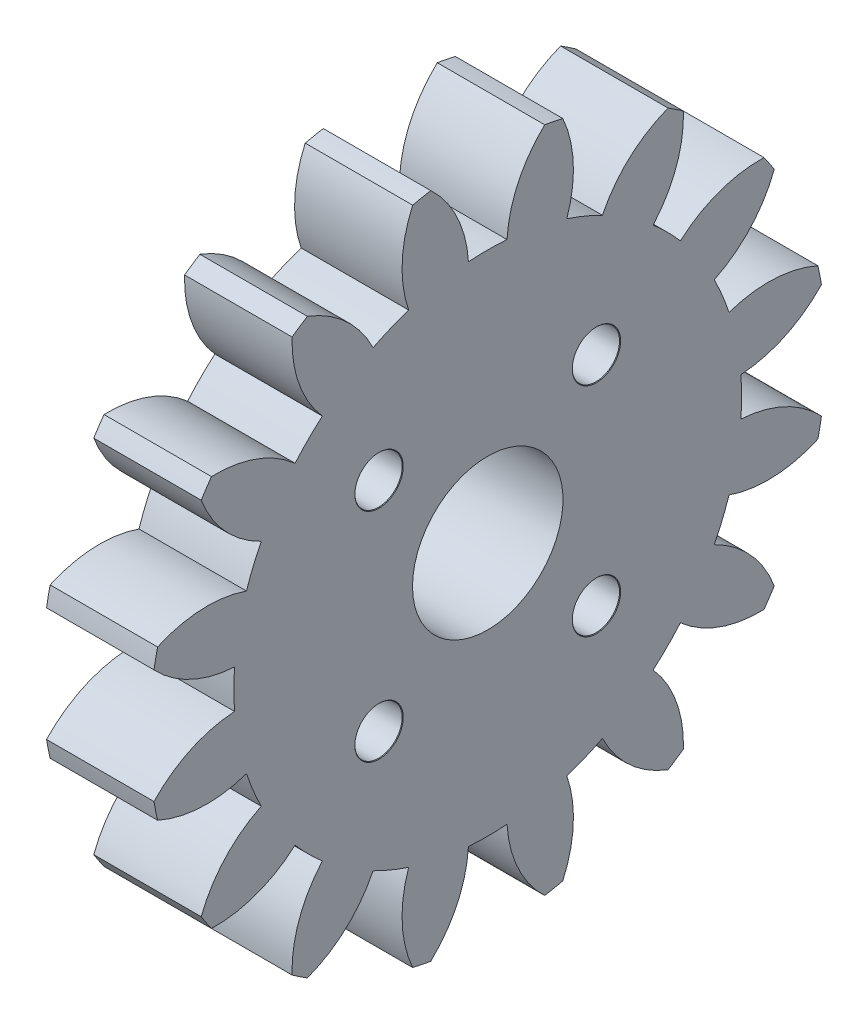
SolidWorks part; units mm, degrees
ref_plane "Plane1" through (0, 0, 0) normal (0, 0, 1) x (1, 0, 0)
ref_plane "Plane2" through (0, 0, 0) normal (0, 1, 0) x (1, 0, 0)
ref_plane "Plane3" through (0, 0, 0) normal (1, 0, 0) x (0, 0, -1)
other "Configuration Table"
sketch "HoldingSke" plane through (0, 0, 0) normal (0, 1, 0) x (1, 0, 0)
  line L0 (0, 0) -> (0.5493, -0.1575)
  line L1 (-15, 0) -> (100, 0) construction
  line L2 (0, 0) -> (-2.1039, 2.3779)
  line L3 (0, 0) -> (-11.863, 4.5341)
  line L4 (0, 0) -> (8.3015, 2.3804)
  line L5 (0, 0) -> (-46.8476, -17.4728)
  line L6 (0, 0) -> (-4.1448, -2.7965)
  line L7 (-2.1039, 2.3779) -> (8.6586, 51.2059)
  line L8 (-76.2, 54.61) -> (-75.2, 54.61)
  line L9 (-71.009, 38.7566) -> (-53.1078, 45.2721)
  line L10 (-76.2, 71.12) -> (104.1128, 71.12)
  line L11 (0, 0) -> (-5, 0)
  line L12 (-76.2, 101.6) -> (-76.147, 101.6)
  line L13 (24.9733, 27.94) -> (52.9518, 28.4284)
  line L14 (24.9733, 27.94) -> (24.9743, 27.94)
  line L15 (24.9733, 27.94) -> (100.4006, 29.5858)
  line L16 (-63.627, -1.75) -> (-12.827, -1.75)
  circle A0 centre (0, 0) radius 3.5
  circle A1 centre (0, 0) radius 11.8115
  circle A2 centre (0, 0) radius 37.5
  circle A3 centre (0, 0) radius 3.5
  dimension "MHD" = 23.623
  dimension "Hub_dia" = 75
  dimension "Bore" = 7
  dimension "MBD" = 7
  dimension "Num_teeth" = 16
  dimension "Pitch" = 0.5714
  dimension "Overall_len" = 50
  dimension "Show_teeth" = 16
  dimension "Thickness" = 5
  dimension "OAL" = 50.0001
  dimension "T_dim" = 1
  dimension "Ap" = 20
  dimension "H" = 19.05
  dimension "Pitch_radius" = 180.3128
  dimension "Width" = 5
  dimension "Backlash" = 0.053
  dimension "Addendum_fac" = 1
  dimension "Dedendum_fac" = 1.25
  dimension "Clearance_fac" = 0.25
  dimension "Dedendum_add" = 0.001
  dimension "Module" = 1.75
sketch "BasProSke" plane through (0, 0, 0) normal (0, 1, 0) x (1, 0, 0)
  line L0 (-10, 0) -> (60, 0) construction
  line L1 (0, 0) -> (0, 15.75)
  line L2 (0, 0) -> (5, 0)
  line L3 (5, 0) -> (5, 15.75)
  line L4 (5, 15.75) -> (0, 15.75)
  dimension "Thickness" = 5
  dimension "Diameter" = 31.5
revolve "Base-Revolve" add sketch "BasProSke" angle 360 about L0
sketch "TooCutSke" plane through (0, 0, 0) normal (1, 0, 0) x (0, 0, -1)
  line L1 (0, 0) -> (0, 107) construction
  line L2 (0, 0) -> (-1.4649, 13.9231) construction
  line L3 (0, 0) -> (-5.4397, 27.3471) construction
  line L4 (-1.4649, 13.9231) -> (-2.7198, 13.6735) construction
  arc A0 (0.8967, 11.7774) -> (-0.8967, 11.7774) centre (0, 0) ccw
  arc A1 (2.6744, 15.5471) -> (-2.6744, 15.5471) centre (0, 0) ccw
  circle A2 centre (0, 0) radius 14 construction
  circle A3 centre (0, 0) radius 13.1557 construction
  arc A4 (-0.8967, 11.7774) -> (-2.6744, 15.5471) centre (-6.4869, 11.4452) ccw
  arc A5 (2.6744, 15.5471) -> (0.8967, 11.7774) centre (6.4869, 11.4452) ccw
  dimension "Root_dia" = 23.623
  dimension "Overcut_dia" = 31.5508
  dimension "Pitch_dia" = 28
  dimension "Base_dia" = 26.3114
  dimension "Flank_rad" = 5.6
  dimension "Half_ang" = 11.25
  dimension "Half_CT" = 1.2795
extrude "ToothCut" cut sketch "TooCutSke" along normal through all
fillet "Breaks" [suppressed] radius 0.035
fillet "RootFillets" [suppressed] radius 0.4385
pattern_circular "TeethCuts" count 16 every 22.5 about axis through (-10, 0, 0) along (1, 0, 0) of "ToothCut", "RootFillets", "Breaks"
sketch "HubNeaOneSke" plane through (0, 0, 0) normal (-1, 0, 0) x (0, 0, 1)
  circle A0 centre (0, 0) radius 11.8115
  dimension "Diameter" = 23.623
extrude "HubNearOne" [suppressed] add sketch "HubNeaOneSke" along normal blind 45.0001
sketch "HubNeaBotSke" plane through (0, 0, 0) normal (-1, 0, 0) x (0, 0, 1)
  circle A0 centre (0, 0) radius 11.8115
  dimension "Diameter" = 23.623
extrude "HubNearBoth" [suppressed] add sketch "HubNeaBotSke" along normal blind 22.5
ref_plane "FarPln" through (5, 0, 0) normal (1, 0, 0) x (0, 0, -1)
sketch "HubFarSke" plane through (5, 0, 0) normal (1, 0, 0) x (0, 0, -1)
  circle A0 centre (0, 0) radius 11.8115
  dimension "Diameter" = 23.623
extrude "HubFar" [suppressed] add sketch "HubFarSke" along normal blind 22.5
sketch "BorSke" plane through (0, 0, 0) normal (1, 0, 0) x (0, 0, -1)
  circle A0 centre (0, 0) radius 3.5
  dimension "Diameter" = 7
extrude "Bore" cut sketch "BorSke" along normal mid plane 100.0001
sketch "KeySke" plane through (0, 0, 0) normal (1, 0, 0) x (0, 0, -1)
  line L0 (-1, 0) -> (-1, 4.5)
  line L1 (-1, 4.5) -> (1, 4.5)
  line L2 (1, 4.5) -> (1, 0)
  line L3 (0, 0) -> (0, 34) construction
  line L4 (-1, 0) -> (1, 0)
  dimension "Offset" = 4.5
  dimension "Width" = 2
extrude "Keyway" [suppressed] cut sketch "KeySke" along normal mid plane 100.0001
pattern_circular "Keyway2" [suppressed] count 2 every 90 about axis through (-10, 0, 0) along (1, 0, 0)
sketch "Sketch2" plane through (5, 0, 0) normal (1, 0, 0) x (0, 0, -1)
  line L1 (-5.0558, -5.0558) -> (5.0558, -5.0558)
  line L2 (-5.0558, -5.0558) -> (-5.0558, 5.0558)
  line L3 (-5.0558, 5.0558) -> (5.0558, 5.0558)
  line L4 (5.0558, -5.0558) -> (5.0558, 5.0558)
  line L5 (-5.0558, -5.0558) -> (5.0558, 5.0558) construction
  line L6 (-5.0558, 5.0558) -> (5.0558, -5.0558) construction
  point P0 (0, 0)
  dimension "D1" = 14.3
  dimension "D2" = 90
hole_wizard "M2 Clearance Hole1" positions "Sketch5" profile "Sketch6" hole size "M2" standard "ANSI Metric" end condition through all
sketch "Sketch5" plane through (5, 0, 0) normal (1, 0, 0) x (0, 0, -1)
  point P0 (-5.0558, 5.0558)
  point P3 (5.0558, 5.0558)
  point P6 (5.0558, -5.0558)
  point P9 (-5.0558, -5.0558)
sketch "Sketch6" plane through (5, 5.0558, 5.0558) normal (0, 1, 0) x (0, 0, -1)
  line L0 (0, 0) -> (0, 5)
  line L1 (0, 5) -> (1.1, 5)
  line L2 (1.1, 5) -> (1.1, 0.025)
  line L3 (1.1, 0.025) -> (1.125, 0)
  line L5 (1.125, 0) -> (0, 0)
  line L6 (-1.1, 0.025) -> (-1.125, 0) construction
  line L11 (0, -6.35) -> (0, 107.95) construction
  dimension "Thru Hole Dia." = 2.2
  dimension "Thru Hole Depth" = 5
  dimension "Near C'Sink Dia." = 2.25
  dimension "Near C'Sink Angle" = 90
equation "' \"Module@HoldingSke\" = 6.35"
equation "' \"Num_teeth@HoldingSke\" = 12"
equation "' \"Ap@HoldingSke\" =  20"
equation "' \"Ap@HoldingSke\" = 20"
equation "' \"Width@HoldingSke\" = 0.5 * 25.4"
equation "' \"Hub_dia@HoldingSke\"= 1 * 25.4"
equation "' \"Hub_dia@HoldingSke\" = 1 * 25.4"
equation "' \"Overall_len@HoldingSke\" = 1.0 * 25.4"
equation "' \"Bore@HoldingSke\" = 0.75 * 25.4"
equation "' \"T_dim@HoldingSke\" = 0.1 * 25.4"
equation "' \"Width@KeySke\" = 0.25 * 25.4"
equation "' \"Show_teeth@HoldingSke\" = 13"
equation "' \"Backlash@HoldingSke\" = 0.009 * 25.4"
equation "' \"Addendum_fac@HoldingSke\" = 1.0"
equation "' \"Dedendum_fac@HoldingSke\" = 1.25"
equation "' \"Dedendum_add@HoldingSke\" = 0.00005 * 25.4"
equation "' \"Clearance_fac@HoldingSke\" = 0.25"
equation "\"Pitch@HoldingSke\" = 1 / \"Module@HoldingSke\""
equation "\"Overcut_dia@TooCutSke\" = (\"Num_teeth@HoldingSke\" + 2 * \"Addendum_fac@HoldingSke\") / \"Pitch@HoldingSke\" + 0.002 * 25.4"
equation "\"Pitch_dia@TooCutSke\" = \"Num_teeth@HoldingSke\" / \"Pitch@HoldingSke\""
equation "\"Base_dia@TooCutSke\" = \"Num_teeth@HoldingSke\" / \"Pitch@HoldingSke\" * cos((\"Ap@HoldingSke\"  * 3.14159265 / 180))"
equation "\"Root_dia@TooCutSke\" = (\"Num_teeth@HoldingSke\" + 2) / \"Pitch@HoldingSke\" - 2 * (\"Addendum_fac@HoldingSke\" + \"Dedendum_fac@HoldingSke\") / \"Pitch@HoldingSke\" - \"Dedendum_add@HoldingSke\" * 2"
equation "\"Half_ang@TooCutSke\" = 180 / \"Num_teeth@HoldingSke\""
equation "\"Half_CT@TooCutSke\" = \"Num_teeth@HoldingSke\" / \"Pitch@HoldingSke\" * sin((3.14159265 / 2 / \"Num_teeth@HoldingSke\")) / 2 - 7 * \"Backlash@HoldingSke\" / 4"
equation "\"Flank_rad@TooCutSke\" = \"Num_teeth@HoldingSke\" / \"Pitch@HoldingSke\" / 5"
equation "\"Radius@RootFillets\" = \"Clearance_fac@HoldingSke\" / \"Pitch@HoldingSke\" + \"Dedendum_add@HoldingSke\""
equation "\"Break_rad@Breaks\" = 0.02 / \"Pitch@HoldingSke\""
equation "\"Thickness@HoldingSke\" = \"Width@HoldingSke\""
equation "\"OAL@HoldingSke\" = \"Thickness@HoldingSke\""
equation "\"MHD@HoldingSke\" = (\"Num_teeth@HoldingSke\" + 2) / \"Pitch@HoldingSke\" - 2 * (\"Addendum_fac@HoldingSke\" + \"Dedendum_fac@HoldingSke\")  / \"Pitch@HoldingSke\" - \"Dedendum_add@HoldingSke\" * 2"
equation "\"MBD@HoldingSke\" = (\"Num_teeth@HoldingSke\" + 2) / \"Pitch@HoldingSke\" - 2 * (\"Addendum_fac@HoldingSke\" + \"Dedendum_fac@HoldingSke\")  / \"Pitch@HoldingSke\" - \"Dedendum_add@HoldingSke\" * 2 - 0.002 * 25.4"
equation "\"MHD@HoldingSke\" = ((sgn( \"MHD@HoldingSke\" - \"Hub_dia@HoldingSke\" )-1)*( \"MHD@HoldingSke\" - \"Hub_dia@HoldingSke\" ))/-2+ \"Hub_dia@HoldingSke\""
equation "\"MBD@HoldingSke\" = ((sgn( \"MBD@HoldingSke\" - \"Bore@HoldingSke\" )-1)*( \"MBD@HoldingSke\" - \"Bore@HoldingSke\" ))/-2+ \"Bore@HoldingSke\""
equation "\"OAL@HoldingSke\" = ((sgn( \"OAL@HoldingSke\" - \"Overall_len@HoldingSke\" )+1)*( \"OAL@HoldingSke\" - \"Overall_len@HoldingSke\" ))/2 + \"Overall_len@HoldingSke\" + 0.000002 * 25.4"
equation "\"Num_teeth@TeethCuts\" = int( \"Show_teeth@HoldingSke\" ) + 1"
equation "\"Num_teeth@TeethCuts\" = ((sgn( \"Num_teeth@TeethCuts\" - \"Num_teeth@HoldingSke\" )-1)*( \"Num_teeth@TeethCuts\" - \"Num_teeth@HoldingSke\" ))/-2+ \"Num_teeth@HoldingSke\""
equation "\"Num_teeth@TeethCuts\" = ((sgn( \"Num_teeth@TeethCuts\" - 2.0)+1)*( \"Num_teeth@TeethCuts\" - 2.0))/2 +2.0"
equation "\"Angle@TeethCuts\" = 360.0 / \"Num_teeth@HoldingSke\""
equation "\"Diameter@BasProSke\" = (\"Num_teeth@HoldingSke\" + 2 * \"Addendum_fac@HoldingSke\") / \"Pitch@HoldingSke\""
equation "\"Thickness@BasProSke\"  = \"Thickness@HoldingSke\""
equation "' \"Fillet_rad@BasProSke\" =  \"Thickness@HoldingSke\" * 0.05"
equation "' \"Fillet_rad@BasProSke\" = \"Thickness@HoldingSke\" * 0.05"
equation "\"MHD@HoldingSke\" = ((sgn( \"MHD@HoldingSke\" - \"Root_dia@TooCutSke\" )-1)*( \"MHD@HoldingSke\" - \"Root_dia@TooCutSke\" ))/-2+ \"Root_dia@TooCutSke\""
equation "\"Diameter@HubNeaOneSke\" = \"MHD@HoldingSke\""
equation "\"Length@HubNearOne\" = \"OAL@HoldingSke\" - \"Thickness@BasProSke\""
equation "\"Diameter@HubNeaBotSke\" = \"MHD@HoldingSke\""
equation "\"Length@HubNearBoth\" = ( \"OAL@HoldingSke\" - \"Thickness@BasProSke\" ) / 2.0"
equation "\"Thickness@FarPln\" = \"Thickness@BasProSke\""
equation "\"Diameter@HubFarSke\" = \"MHD@HoldingSke\""
equation "\"Length@HubFar\" = ( \"OAL@HoldingSke\" - \"Thickness@BasProSke\" ) / 2.0"
equation "\"Diameter@BorSke\" = \"MBD@HoldingSke\""
equation "\"D1@Bore\" = \"OAL@HoldingSke\" * 2.0"
equation "\"D1@Keyway\" = \"OAL@HoldingSke\" * 2.0"
equation "\"Offset@KeySke\" = \"T_dim@HoldingSke\" + \"MBD@HoldingSke\" / 2.0"
